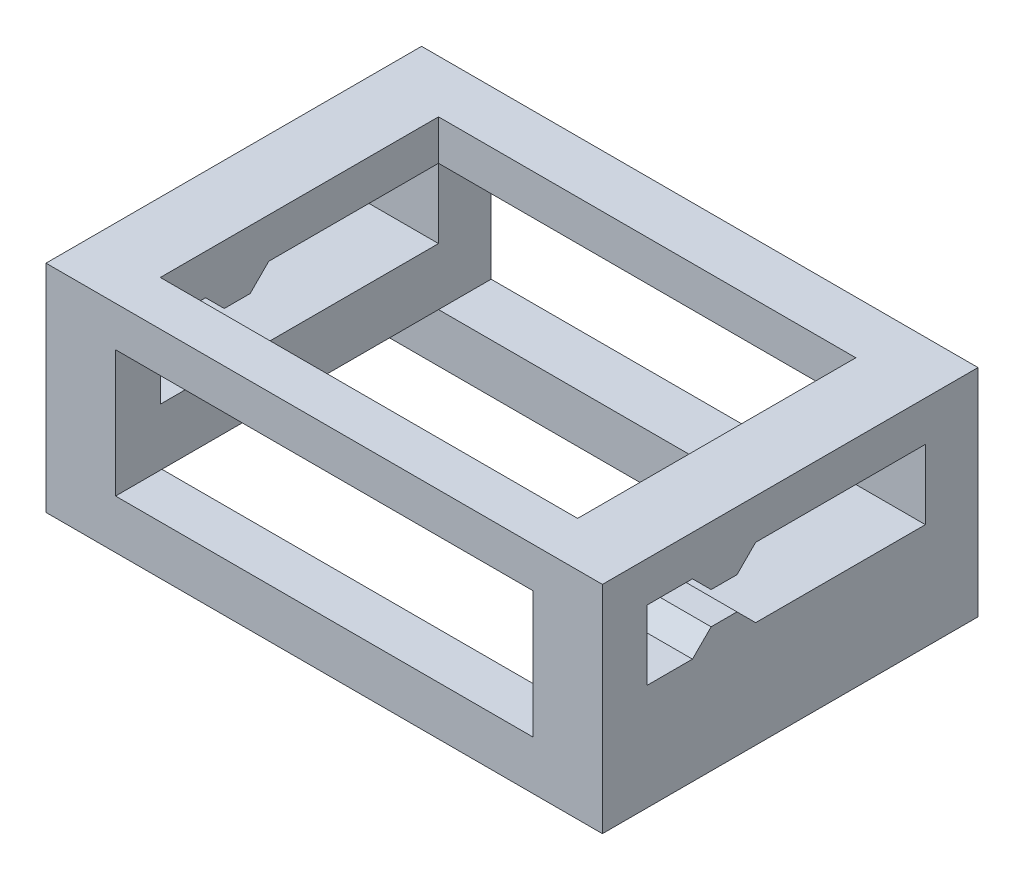
SolidWorks part; units mm, degrees
other "Markup1"
sketch "Sketch4" plane through (5, 30, 10) normal (0.9006, 0.1104, 0.4203) x (0.4243, -0.0149, -0.9054)
ref_plane "Front Plane" through (0, 0, 0) normal (0, 0, 1) x (1, 0, 0)
ref_plane "Top Plane" through (0, 0, 0) normal (0, 1, 0) x (1, 0, 0)
ref_plane "Right Plane" through (0, 0, 0) normal (1, 0, 0) x (0, 0, -1)
sketch "Sketch5" plane through (0, 0, 0) normal (1, 0, 0) x (0, 0, -1)
  line L0 (79.6063, 44.3441) -> (99.6063, 44.3441)
  line L1 (-40, -10) -> (0, -10)
  line L2 (-40, -10) -> (-40, 50)
  line L3 (-7.7972, 50) -> (290, 50)
  line L4 (290, -10) -> (290, 50)
  line L5 (4.6063, 44.3441) -> (24.6063, 44.3441)
  line L6 (4.6063, 44.3441) -> (4.6063, 39.3441)
  line L7 (4.6063, 39.3441) -> (24.6063, 39.3441)
  line L8 (24.6063, 44.3441) -> (24.6063, 39.3441)
  line L10 (-40, 50) -> (-40, 69.4281)
  line L11 (-30, 79.4281) -> (-17.7972, 79.4281)
  line L12 (-7.7972, 50) -> (-7.7972, 69.4281)
  line L13 (99.6063, 44.3441) -> (99.6063, 39.3441)
  line L14 (-30.2972, 66.8499) -> (-17.6377, 66.8499)
  line L15 (-30.2972, 66.8499) -> (-30.2972, 59.8168)
  line L16 (-30.2972, 59.8168) -> (-17.6377, 59.8168)
  line L17 (-17.6377, 66.8499) -> (-17.6377, 59.8168)
  line L18 (79.6063, 39.3441) -> (99.6063, 39.3441)
  line L19 (79.6063, 44.3441) -> (79.6063, 39.3441)
  line L20 (154.6063, 44.3441) -> (174.6063, 44.3441)
  line L21 (174.6063, 44.3441) -> (174.6063, 39.3441)
  line L22 (154.6063, 39.3441) -> (174.6063, 39.3441)
  line L23 (154.6063, 44.3441) -> (154.6063, 39.3441)
  line L24 (229.6063, 44.3441) -> (249.6063, 44.3441)
  line L25 (249.6063, 44.3441) -> (249.6063, 39.3441)
  line L26 (229.6063, 39.3441) -> (249.6063, 39.3441)
  line L27 (229.6063, 44.3441) -> (229.6063, 39.3441)
  line L28 (125, -10) -> (125, 125.6475) construction
  line L30 (0, 0) -> (0, 10)
  line L31 (0, 10) -> (5, 10)
  line L32 (5, 0) -> (5, 10)
  line L33 (245, 0) -> (245, 10)
  line L34 (250, 10) -> (245, 10)
  line L35 (250, 0) -> (250, 10)
  line L37 (0, 0) -> (0, -10)
  line L39 (5, -10) -> (5, 0)
  line L40 (5, -10) -> (245, -10)
  line L42 (245, 0) -> (245, -10)
  line L44 (250, 0) -> (250, -10)
  line L45 (250, -10) -> (290, -10)
  circle A0 centre (-25, 35) radius 3
  circle A1 centre (275, 35) radius 3
  arc A3 (-30, 79.4281) -> (-40, 69.4281) centre (-30, 69.4281) ccw
  arc A4 (-7.7972, 69.4281) -> (-17.7972, 79.4281) centre (-17.7972, 69.4281) ccw
  dimension "D1" = 6
  dimension "D2" = 6
  dimension "D10" = 10
  dimension "D9" = 10
  dimension "D3" = 300
  dimension "D4" = 60
  dimension "D5" = 15
  dimension "D6" = 15
  dimension "D7" = 15
  dimension "D8" = 20
  dimension "D12" = 5
  dimension "D13" = 10
  dimension "D14" = 10
  dimension "D15" = 40
  dimension "D16" = 22.5
  dimension "D17" = 60
  dimension "D18" = 19.4281
  dimension "D11" = 4
extrude "Boss-Extrude1" add sketch "Sketch5" along normal blind 5
sketch "Sketch6" plane through (5, 0, 0) normal (1, 0, 0) x (0, 0, -1)
  line L1 (-40, -10) -> (290, -10)
  line L2 (-40, -10) -> (-40, -25)
  line L3 (-40, -25) -> (290, -25)
  line L4 (290, -10) -> (290, -25)
  dimension "D1" = 15
extrude "Boss-Extrude2" add sketch "Sketch6" against normal blind 5
sketch "Sketch8" plane through (5, 0, 0) normal (1, 0, 0) x (0, 0, -1)
  line L0 (-40, -25) -> (290, -25) construction
  line L1 (48.9686, 27.8258) -> (48.9686, -37.9063) construction
  line L2 (30.9686, 16) -> (66.9686, -20) construction
  line L3 (30.9686, -20) -> (66.9686, 16) construction
  circle A1 centre (30.9686, 16) radius 2
  circle A2 centre (30.9686, -20) radius 2
  circle A3 centre (66.9686, -20) radius 2
  circle A4 centre (66.9686, 16) radius 2
  circle A5 centre (48.9686, -2) radius 3.1
  dimension "D1" = 4
  dimension "D2" = 4
  dimension "D6" = 6.2
  dimension "D3" = 36
  dimension "D4" = 5
  dimension "D5" = 18
extrude "Cut-Extrude1" cut sketch "Sketch8" against normal blind 5
sketch "Sketch9" plane through (5, 0, 0) normal (1, 0, 0) x (0, 0, -1)
  line L0 (290, 50) -> (-7.7972, 50) construction
  line L1 (114.6063, 50) -> (141.6063, 50)
  line L2 (114.6063, 50) -> (114.6063, 62)
  line L3 (114.6063, 62) -> (141.6063, 62)
  line L4 (141.6063, 50) -> (141.6063, 62)
  line L7 (121.0793, 59.1099) -> (122.4214, 57.7678)
  line L8 (117.8239, 59.1099) -> (121.0793, 59.1099)
  line L9 (117.8239, 59.1099) -> (117.8239, 54.1099)
  line L10 (117.8239, 54.1099) -> (121.0793, 54.1099)
  line L11 (137.8239, 59.1099) -> (137.8239, 54.1099)
  line L12 (122.4214, 57.7678) -> (124.28, 57.7678)
  line L13 (124.28, 57.7678) -> (125.6221, 59.1099)
  line L14 (117.8239, 56.6099) -> (119.2503, 56.6099) construction
  line L15 (124.28, 55.452) -> (125.6221, 54.1099)
  line L16 (122.4214, 55.452) -> (124.28, 55.452)
  line L17 (121.0793, 54.1099) -> (122.4214, 55.452)
  line L18 (125.6221, 59.1099) -> (137.8239, 59.1099)
  line L19 (125.6221, 54.1099) -> (137.8239, 54.1099)
  dimension "D1" = 27
  dimension "D2" = 12
  dimension "D3" = 20
  dimension "D4" = 5
extrude "Boss-Extrude3" add sketch "Sketch9" against normal blind 5
sketch "Sketch10" plane through (5, 0, 0) normal (1, 0, 0) x (0, 0, -1)
  line L1 (114.6063, 62) -> (117.8239, 62)
  line L2 (114.6063, 62) -> (114.6063, 59.1099)
  line L3 (114.6063, 59.1099) -> (117.8239, 59.1099)
  line L4 (117.8239, 62) -> (117.8239, 59.1099)
  line L5 (141.6063, 62) -> (137.8239, 62)
  line L6 (141.6063, 62) -> (141.6063, 59.1099)
  line L7 (141.6063, 59.1099) -> (137.8239, 59.1099)
  line L8 (137.8239, 62) -> (137.8239, 59.1099)
  line L9 (141.6063, 50) -> (137.8239, 50)
  line L10 (141.6063, 50) -> (141.6063, 46.4787)
  line L11 (141.6063, 46.4787) -> (137.8239, 46.4787)
  line L12 (137.8239, 50) -> (137.8239, 46.4787)
  line L13 (114.6063, 50) -> (117.9392, 50)
  line L14 (114.6063, 50) -> (114.6063, 46.4787)
  line L15 (114.6063, 46.4787) -> (117.9392, 46.4787)
  line L16 (117.9392, 50) -> (117.9392, 46.4787)
  point P22 (117.9392, 50)
extrude "Boss-Extrude4" add sketch "Sketch10" along normal blind 30
sketch "Sketch13" plane through (35, 0, 0) normal (1, 0, 0) x (0, 0, -1)
  line L0 (114.6063, 46.4787) -> (117.9392, 46.4787) construction
  line L1 (114.6063, 46.4787) -> (141.6063, 46.4787)
  line L2 (117.8239, 54.1099) -> (121.0793, 54.1099) construction
  line L3 (121.0793, 54.1099) -> (122.4214, 55.452) construction
  line L4 (114.6063, 62) -> (114.6063, 59.1099)
  line L5 (114.6063, 59.1099) -> (117.8239, 59.1099)
  line L6 (117.8239, 59.1099) -> (117.8239, 62)
  line L7 (117.8239, 62) -> (114.6063, 62)
  line L8 (114.6063, 62) -> (114.6063, 46.4787)
  line L11 (117.8239, 62) -> (114.6063, 62)
  line L12 (124.28, 55.452) -> (125.6221, 54.1099) construction
  line L13 (122.4214, 55.452) -> (124.28, 55.452) construction
  line L14 (137.8239, 54.1099) -> (137.8239, 59.1099) construction
  line L15 (125.6221, 59.1099) -> (124.28, 57.7678) construction
  line L16 (124.28, 57.7678) -> (122.4214, 57.7678) construction
  line L17 (122.4214, 57.7678) -> (121.0793, 59.1099) construction
  line L18 (121.0793, 59.1099) -> (117.8239, 59.1099) construction
  line L19 (117.8239, 59.1099) -> (117.8239, 54.1099) construction
  line L20 (125.6221, 54.1099) -> (137.8239, 54.1099) construction
  line L21 (137.8239, 59.1099) -> (125.6221, 59.1099) construction
  line L22 (141.6063, 62) -> (137.8239, 62) construction
  line L23 (141.6063, 46.4787) -> (141.6063, 50) construction
  line L24 (117.8239, 54.1099) -> (121.0793, 54.1099)
  line L25 (121.0793, 54.1099) -> (122.4214, 55.452)
  line L26 (124.28, 55.452) -> (125.6221, 54.1099)
  line L27 (122.4214, 55.452) -> (124.28, 55.452)
  line L28 (137.8239, 54.1099) -> (137.8239, 59.1099)
  line L29 (125.6221, 59.1099) -> (124.28, 57.7678)
  line L30 (124.28, 57.7678) -> (122.4214, 57.7678)
  line L31 (122.4214, 57.7678) -> (121.0793, 59.1099)
  line L32 (121.0793, 59.1099) -> (117.8239, 59.1099)
  line L33 (117.8239, 59.1099) -> (117.8239, 54.1099)
  line L34 (125.6221, 54.1099) -> (137.8239, 54.1099)
  line L35 (137.8239, 59.1099) -> (125.6221, 59.1099)
  line L36 (141.6063, 62) -> (117.8239, 62)
  line L37 (141.6063, 46.4787) -> (141.6063, 62)
  point P1 (141.9269, 46.4787)
  point P4 (141.6063, 61.6412)
  point P8 (114.6063, 46.8888)
  point P20 (118.1446, 62)
  dimension "D1" = 0
extrude "Boss-Extrude6" add sketch "Sketch13" along normal blind 5
sketch "Sketch14" plane through (0, 0, 0) normal (-1, 0, 0) x (0, 0, 1)
  line L0 (-141.6063, 50) -> (-114.6063, 50)
  line L10 (-290, -25) -> (40, -25)
  line L11 (40, -25) -> (40, 69.4281)
  line L12 (30, 79.4281) -> (17.7972, 79.4281)
  line L13 (7.7972, 69.4281) -> (7.7972, 50)
  line L14 (7.7972, 50) -> (-114.6063, 50)
  line L15 (-114.6063, 50) -> (-114.6063, 62)
  line L16 (-114.6063, 62) -> (-141.6063, 62)
  line L17 (-141.6063, 62) -> (-141.6063, 50)
  line L18 (-141.6063, 50) -> (-290, 50)
  line L19 (-290, 50) -> (-290, -25)
  line L20 (-290, -25) -> (40, -25)
  line L21 (40, -25) -> (40, 69.4281)
  line L22 (30, 79.4281) -> (17.7972, 79.4281)
  line L23 (7.7972, 69.4281) -> (7.7972, 50)
  line L24 (7.7972, 50) -> (-114.6063, 50)
  line L28 (-141.6063, 50) -> (-290, 50)
  line L29 (-290, 50) -> (-290, -25)
  arc A2 (40, 69.4281) -> (30, 79.4281) centre (30, 69.4281) ccw
  arc A3 (17.7972, 79.4281) -> (7.7972, 69.4281) centre (17.7972, 69.4281) ccw
  arc A4 (40, 69.4281) -> (30, 79.4281) centre (30, 69.4281) ccw
  arc A5 (17.7972, 79.4281) -> (7.7972, 69.4281) centre (17.7972, 69.4281) ccw
  dimension "D1" = 0
extrude "Cut-Extrude4" cut sketch "Sketch14" against normal blind 14.3
sketch "Sketch15" plane through (14.3, 0, 0) normal (-1, 0, 0) x (0, 0, 1)
  line L1 (-117.9392, 50) -> (-114.6063, 50)
  line L2 (-117.9392, 50) -> (-117.9392, 46.4787)
  line L3 (-117.9392, 46.4787) -> (-114.6063, 46.4787)
  line L4 (-141.6063, 46.4787) -> (-137.8239, 46.4787)
  line L5 (-137.8239, 46.4787) -> (-137.8239, 50)
  line L6 (-137.8239, 50) -> (-141.6063, 50)
  line L7 (-141.6063, 50) -> (-141.6063, 46.4787)
  line L8 (-141.6063, 46.4787) -> (-137.8239, 46.4787)
  line L9 (-137.8239, 46.4787) -> (-137.8239, 50)
  line L10 (-137.8239, 50) -> (-141.6063, 50)
  line L11 (-141.6063, 50) -> (-141.6063, 46.4787)
  line L12 (-114.6063, 50) -> (-114.6063, 46.4787)
  dimension "D1" = 0
extrude "Boss-Extrude9" add sketch "Sketch15" along normal blind 14.3
